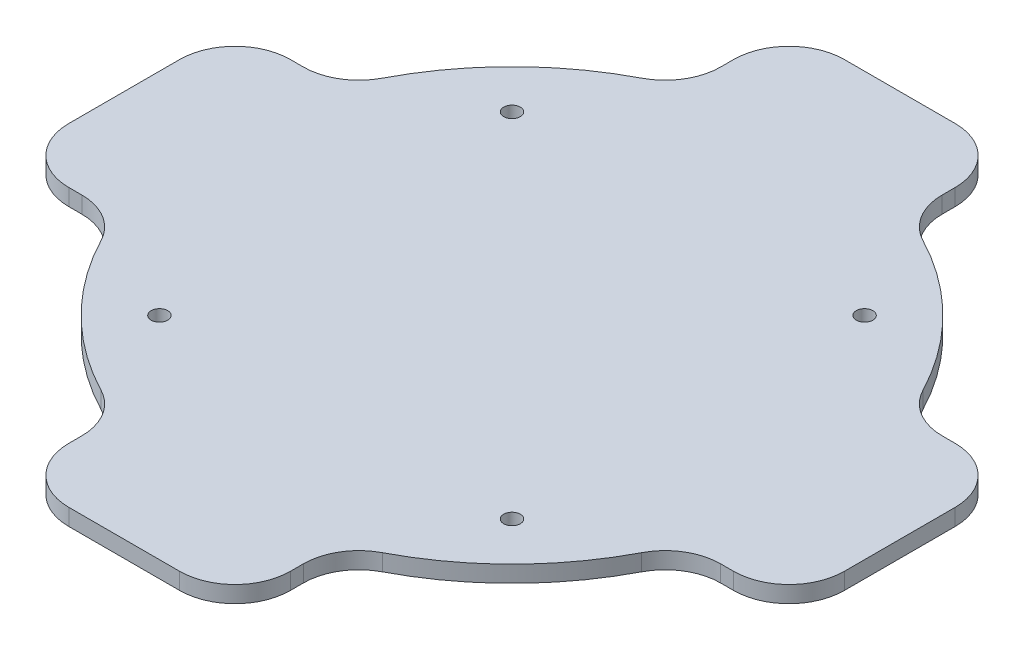
SolidWorks part; units mm, degrees
ref_plane "前视基准面" through (0, 0, 0) normal (0, 0, 1) x (1, 0, 0)
ref_plane "上视基准面" through (0, 0, 0) normal (0, 1, 0) x (1, 0, 0)
ref_plane "右视基准面" through (0, 0, 0) normal (1, 0, 0) x (0, 0, -1)
sketch "草图1" plane through (0, 0, 0) normal (0, 1, 0) x (1, 0, 0)
  line L2 (0, 0) -> (0, -10)
  line L3 (28.8314, -10) -> (30, -10)
  line L4 (35, 0) -> (35, -5)
  line L6 (35, 0) -> (35, 5)
  line L7 (30, 10) -> (28.8314, 10)
  line L8 (0, 0) -> (0, 10)
  line L9 (-10, -28.8314) -> (-10, -30)
  line L10 (0, -35) -> (-5, -35)
  line L12 (0, -35) -> (5, -35)
  line L13 (10, -30) -> (10, -28.8314)
  line L15 (-28.8314, 10) -> (-30, 10)
  line L16 (-35, 0) -> (-35, 5)
  line L18 (-35, 0) -> (-35, -5)
  line L19 (-30, -10) -> (-28.8314, -10)
  line L21 (10, 28.8314) -> (10, 30)
  line L22 (0, 35) -> (5, 35)
  line L24 (0, 35) -> (-5, 35)
  line L25 (-10, 30) -> (-10, 28.8314)
  arc A0 (24.3958, 12.6923) -> (12.6923, 24.3958) centre (0, 0) ccw
  arc A6 (30, -10) -> (35, -5) centre (30, -5) ccw
  arc A7 (35, 5) -> (30, 10) centre (30, 5) ccw
  arc A11 (24.3958, -12.6923) -> (28.8314, -10) centre (28.8314, -15) cw
  arc A12 (24.3958, 12.6923) -> (28.8314, 10) centre (28.8314, 15) ccw
  arc A14 (-10, -30) -> (-5, -35) centre (-5, -30) ccw
  arc A15 (5, -35) -> (10, -30) centre (5, -30) ccw
  arc A17 (-12.6923, -24.3958) -> (-10, -28.8314) centre (-15, -28.8314) cw
  arc A18 (12.6923, -24.3958) -> (10, -28.8314) centre (15, -28.8314) ccw
  arc A20 (-30, 10) -> (-35, 5) centre (-30, 5) ccw
  arc A21 (-35, -5) -> (-30, -10) centre (-30, -5) ccw
  arc A23 (-24.3958, 12.6923) -> (-28.8314, 10) centre (-28.8314, 15) cw
  arc A24 (-24.3958, -12.6923) -> (-28.8314, -10) centre (-28.8314, -15) ccw
  arc A26 (10, 30) -> (5, 35) centre (5, 30) ccw
  arc A27 (-5, 35) -> (-10, 30) centre (-5, 30) ccw
  arc A29 (12.6923, 24.3958) -> (10, 28.8314) centre (15, 28.8314) cw
  arc A30 (-12.6923, 24.3958) -> (-10, 28.8314) centre (-15, 28.8314) ccw
  arc A31 (-12.6923, 24.3958) -> (-24.3958, 12.6923) centre (0, 0) ccw
  arc A32 (12.6923, -24.3958) -> (24.3958, -12.6923) centre (0, 0) ccw
  arc A33 (-24.3958, -12.6923) -> (-12.6923, -24.3958) centre (0, 0) ccw
  circle A34 centre (15.9099, -15.9099) radius 0.75
  circle A35 centre (-15.9099, -15.9099) radius 0.75
  circle A36 centre (-15.9099, 15.9099) radius 0.75
  circle A37 centre (15.9099, 15.9099) radius 0.75
  point P15 (0, 0)
  point P20 (0, 0)
  point P96 (0, 0)
  dimension "D1" = 4
  dimension "D2" = 5
  dimension "D3" = 5
  dimension "D4" = 4
extrude "凸台-拉伸2" add sketch "草图1" along normal blind 1.5
